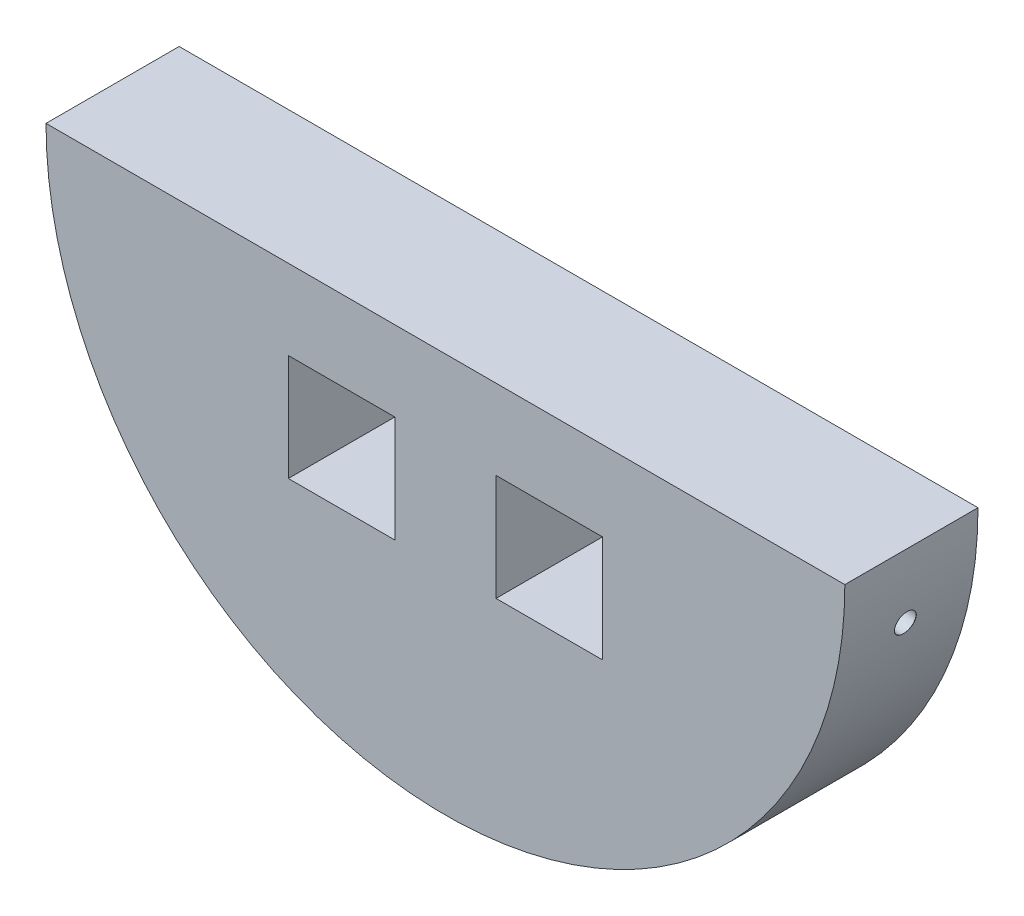
SolidWorks part; units mm, degrees
ref_plane "Front Plane" through (0, 0, 0) normal (0, 0, 1) x (1, 0, 0)
ref_plane "Top Plane" through (0, 0, 0) normal (0, 1, 0) x (1, 0, 0)
ref_plane "Right Plane" through (0, 0, 0) normal (1, 0, 0) x (0, 0, -1)
sketch "Sketch1" plane through (0, 0, 0) normal (0, 0, 1) x (1, 0, 0)
  line L0 (-150, 0) -> (0, 0)
  line L3 (-65.5, -35) -> (-45.5, -35)
  line L4 (-65.5, -35) -> (-65.5, -15)
  line L5 (-65.5, -15) -> (-45.5, -15)
  line L6 (-45.5, -35) -> (-45.5, -15)
  line L7 (-104.5, -35) -> (-84.5, -35)
  line L8 (-104.5, -35) -> (-104.5, -15)
  line L9 (-104.5, -15) -> (-84.5, -15)
  line L10 (-84.5, -35) -> (-84.5, -15)
  arc A1 (-150, 0) -> (0, 0) centre (-75, 0) ccw
  dimension "D1" = 19
  dimension "D7" = 75
  dimension "D2" = 15
  dimension "D3" = 9.5
  dimension "D4" = 20
extrude "Boss-Extrude1" add sketch "Sketch1" along normal blind 25
hole_wizard "Ø4.0mm Dowel Hole2" positions "3DSketch2" profile "Sketch4" hole size "Ø4.0" standard "ANSI Metric"
sketch3d "3DSketch2"
  line L2 (0, 0, 25) -> (0, 0, 0) construction
  line L4 (0, 0, 25) -> (0, 0, 0) construction
  line L5 (0, 0, 12.5) -> (-1.1394, -13.0236, 12.5) construction
  line L8 (-75, 0, 0) -> (-75, 0, 25) construction
  line L9 (0, 0, 0) -> (-150, 0, 0) construction
  line L10 (0, 0, 25) -> (-150, 0, 25) construction
  line L12 (-75, 0, 12.5) -> (-1.1394, -13.0236, 12.5) construction
  line L16 (-75, 0, 12.5) -> (0, 0, 12.5) construction
  point P0 (-1.1394, -13.0236, 12.5)
  point P16 (-1.1394, -13.0236, 12.5)
  point P23 (-1.1394, -13.0236, 12.5)
  point P25 (-1.1394, -13.0236, 12.5)
  dimension "D1" = 10
sketch "Sketch4" plane through (-1.1394, -13.0236, 12.5) normal (0, 0, 1) x (0.1736, 0.9848, 0)
  line L0 (0, 0) -> (0, 17.2017)
  line L1 (0, 17.2017) -> (2, 16)
  line L2 (2, 16) -> (2, 0.025)
  line L3 (2, 0.025) -> (2.025, 0)
  line L5 (2.025, 0) -> (0, 0)
  line L6 (-2, 0.025) -> (-2.025, 0) construction
  line L10 (0, 17.2017) -> (-2, 16) construction
  line L11 (0, -6.35) -> (0, 107.95) construction
  dimension "Hole Dia." = 4
  dimension "Hole Depth" = 16
  dimension "Near C'Sink Dia." = 4.05
  dimension "Near C'Sink Angle" = 90
  dimension "Drill Angle" = 118
pattern_circular "CirPattern1" count 5 over 160 about axis through (-75, 0, 0) along (0, 0, 1) of "Ø4.0mm Dowel Hole2"
